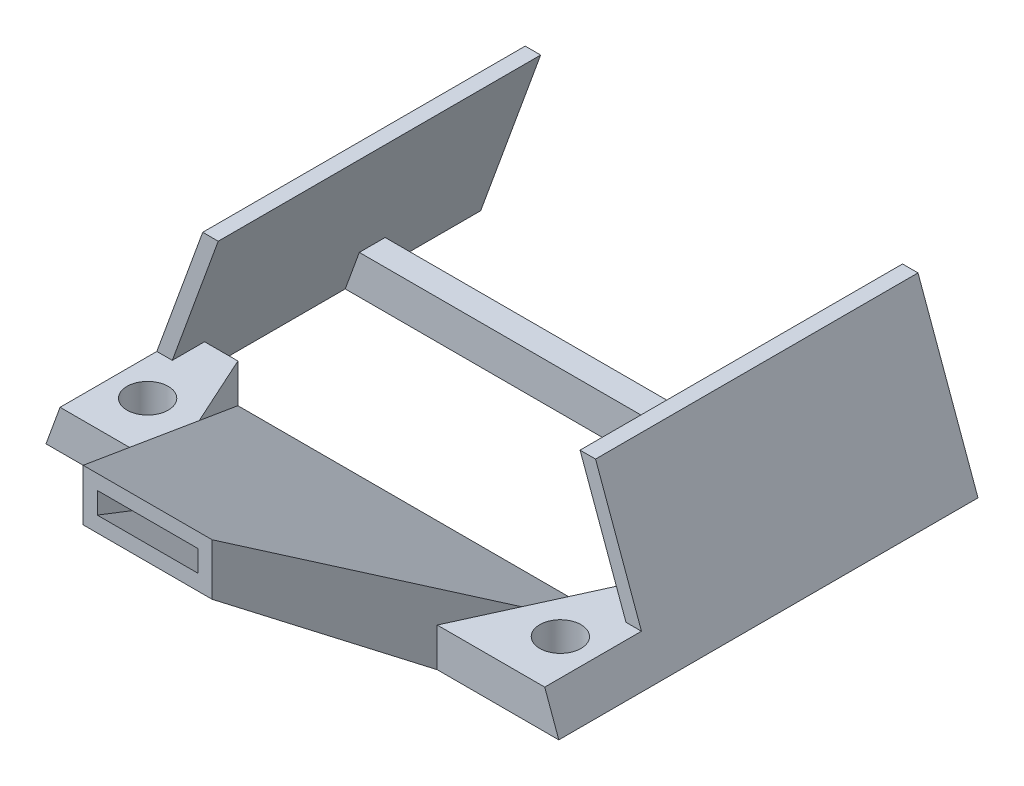
SolidWorks part; units mm, degrees
ref_plane "前基準面" through (0, 0, 0) normal (0, 0, 1) x (1, 0, 0)
ref_plane "上基準面" through (0, 0, 0) normal (0, 1, 0) x (1, 0, 0)
ref_plane "右基準面" through (0, 0, 0) normal (1, 0, 0) x (0, 0, -1)
sketch "草圖1" plane through (0, 0, 0) normal (0, 1, 0) x (1, 0, 0)
  line L1 (-20, 20) -> (20, 20) construction
  line L2 (-20, 20) -> (-20, -20) construction
  line L3 (-20, -20) -> (20, -20) construction
  line L4 (20, 20) -> (20, -20) construction
  line L5 (-20, 20) -> (20, -20) construction
  line L6 (-20, -20) -> (20, 20) construction
  circle A0 centre (0, 0) radius 20 construction
  circle A1 centre (0, 0) radius 10 construction
  circle A2 centre (-16, -16) radius 1.5 construction
  circle A3 centre (16, -16) radius 1.5 construction
  point P0 (0, 0)
  point P13 (0, 0)
  dimension "D3" = 10
  dimension "D4" = 3
  dimension "D5" = 32
  dimension "D1" = 40
  dimension "D2" = 40
sketch "草圖2" plane through (0, 0, 0) normal (1, 0, 0) x (0, 0, -1)
  line L0 (-20, 0) -> (-10, 0)
  line L1 (-20, 0) -> (20, 0) construction
  line L2 (20, 0) -> (-20, 0) construction
  line L3 (-20, 0) -> (-32, 8)
  line L4 (-32, 8) -> (-32, 12)
  line L5 (-32, 12) -> (-10, 0)
  dimension "D1" = 10
  dimension "D2" = 12
  dimension "D3" = 12
  dimension "D4" = 4
extrude "填料-伸長3" add sketch "草圖2" along normal mid plane 30
sketch "草圖3" plane through (0, 0, 0) normal (0, 1, 0) x (1, 0, 0)
  line L0 (-15, -10) -> (-15, -32)
  line L1 (15, -32) -> (-15, -32) construction
  line L2 (-15, -10) -> (-15, -32) construction
  line L3 (-15, -32) -> (-5, -32)
  line L4 (-5, -32) -> (-15, -10)
  line L5 (0, 4.8792) -> (0, -34.7283) construction
  line L6 (5, -32) -> (15, -10)
  line L7 (15, -32) -> (5, -32)
  line L8 (15, -10) -> (15, -32)
  dimension "D1" = 10
extrude "除料-伸長1" cut sketch "草圖3" along normal blind 30
shell "薄殼3" thickness 1
sketch "草圖5" plane through (0, 0, 0) normal (0, 0, 1) x (1, 0, 0)
  line L0 (-19.8782, 0) -> (-15.2264, 12.7805)
  line L1 (-20, 0) -> (20, 0) construction
  line L2 (-15.2264, 12.7805) -> (-14.0264, 12.7805)
  line L3 (-14.0264, 12.7805) -> (-18.6782, 0)
  line L4 (-18.6782, 0) -> (-19.8782, 0)
  line L5 (0, 19.9849) -> (0, -5.252) construction
  line L6 (18.6782, 0) -> (19.8782, 0)
  line L7 (14.0264, 12.7805) -> (18.6782, 0)
  line L8 (15.2264, 12.7805) -> (14.0264, 12.7805)
  line L9 (19.8782, 0) -> (15.2264, 12.7805)
  dimension "D1" = 70
  dimension "D2" = 1.2
extrude "填料-伸長4" add sketch "草圖5" along normal mid plane 25 separate body
sketch "草圖6" plane through (0, 0, 0) normal (0, 1, 0) x (1, 0, 0)
  line L0 (-20, -10) -> (-15, -10)
  line L1 (-20, 20) -> (-20, -20) construction
  line L2 (-15, -10) -> (-10.4545, -20)
  line L3 (-10.4545, -20) -> (-20, -20)
  line L4 (-20, -20) -> (-20, -10)
  line L5 (0, 4.6794) -> (0, -25.0724) construction
  line L6 (20, -20) -> (20, -10)
  line L7 (10.4545, -20) -> (20, -20)
  line L8 (15, -10) -> (10.4545, -20)
  line L9 (20, -10) -> (15, -10)
  line L10 (20, 20) -> (20, -20) construction
  line L11 (-20, 4) -> (20, 4)
  line L12 (-20, 4) -> (-20, 2)
  line L13 (-20, 2) -> (20, 2)
  line L14 (20, 4) -> (20, 2)
  circle A0 centre (-16, -16) radius 1.6
  circle A1 centre (16, -16) radius 1.6
  dimension "D1" = 3.2
  dimension "D2" = 2
  dimension "D3" = 2
extrude "填料-伸長5" add sketch "草圖6" along normal blind 3
sketch "草圖7" plane through (0, 0, -12.5) normal (0, 0, -1) x (-1, 0, 0)
  line L0 (-20, 3) -> (-18.7862, 3)
  line L2 (-18.7862, 3) -> (-19.8782, 0)
  line L3 (-19.8782, 0) -> (-20, 0)
  line L4 (-20, 0) -> (-20, 3)
  line L5 (0, 8.3431) -> (0, -5.2173) construction
  line L6 (20, 0) -> (20, 3)
  line L7 (19.8782, 0) -> (20, 0)
  line L8 (18.7862, 3) -> (19.8782, 0)
  line L9 (20, 3) -> (18.7862, 3)
extrude "除料-伸長2" cut sketch "草圖7" against normal blind 61
